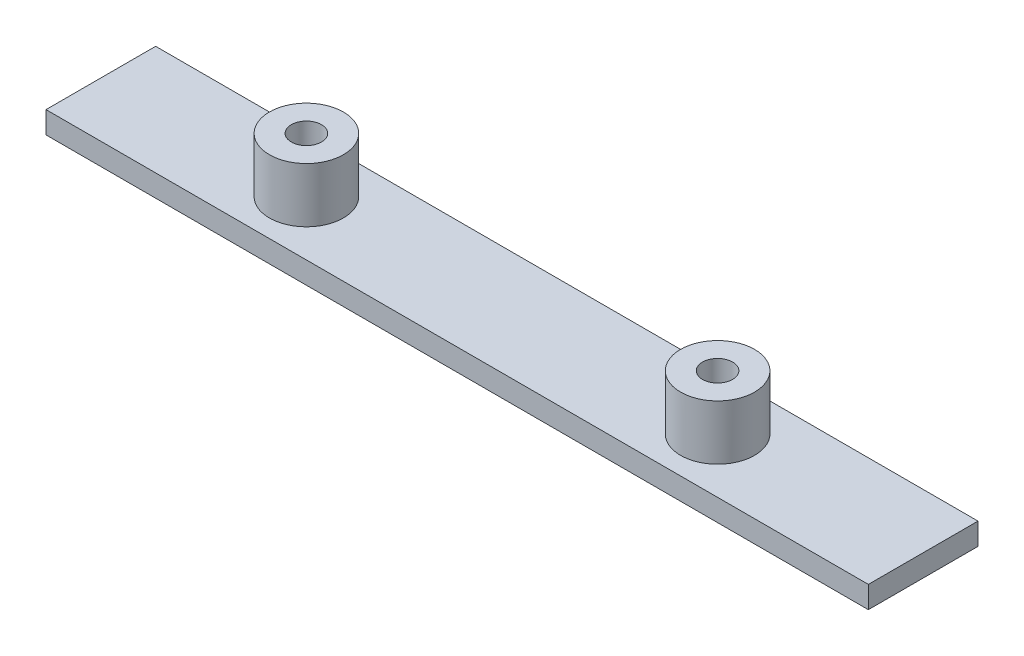
SolidWorks part; units mm, degrees
material "1060 Alloy"
ref_plane "Front Plane" through (0, 0, 0) normal (0, 0, 1) x (1, 0, 0)
ref_plane "Top Plane" through (0, 0, 0) normal (0, 1, 0) x (1, 0, 0)
ref_plane "Right Plane" through (0, 0, 0) normal (1, 0, 0) x (0, 0, -1)
sketch "Sketch1" plane through (0, 0, 0) normal (0, 0, 1) x (1, 0, 0)
  line L0 (-37.5, 0) -> (37.5, 0)
  line L1 (37.5, 2) -> (37.5, 0)
  line L2 (-37.5, 11) -> (-37.5, -4) construction
  line L3 (-37.5, 2) -> (-37.5, 0)
  line L5 (37.5, 2) -> (-37.5, 2)
  line L6 (0, 0) -> (0, 2) construction
  dimension "D1" = 2
extrude "Boss-Extrude1" add sketch "Sketch1" along normal up to surface (10 mm away)
sketch "Sketch2" plane through (0, 2, 0) normal (0, 1, 0) x (1, 0, 0)
  line L0 (0, 0) -> (0, -10) construction
  line L1 (37.5, -10) -> (37.5, 0) construction
  line L3 (37.5, -10) -> (-37.5, -10) construction
  line L4 (0, -5) -> (37.5, -5) construction
  line L6 (0, -10) -> (37.5, -10) construction
  line L7 (37.5, -10) -> (37.5, 0) construction
  line L8 (37.5, 0) -> (0, 0) construction
  line L9 (18.75, -10) -> (18.75, 0) construction
  circle A0 centre (18.75, -5) radius 1.375
  circle A1 centre (18.75, -5) radius 3.375
  circle A2 centre (18.75, -5) radius 1.375 construction
  circle A3 centre (-18.75, -5) radius 1.375
  circle A4 centre (-18.75, -5) radius 3.375
  dimension "D1" = 2
extrude "Boss-Extrude2" add sketch "Sketch2" along normal blind 5
sketch "Sketch3" plane through (0, 2, 0) normal (0, 1, 0) x (1, 0, 0)
  circle A0 centre (18.75, -5) radius 1.375
  circle A1 centre (-18.75, -5) radius 1.375
  circle A2 centre (18.75, -5) radius 1.375 construction
  circle A3 centre (-18.75, -5) radius 1.375 construction
extrude "Cut-Extrude1" cut sketch "Sketch3" against normal through all
